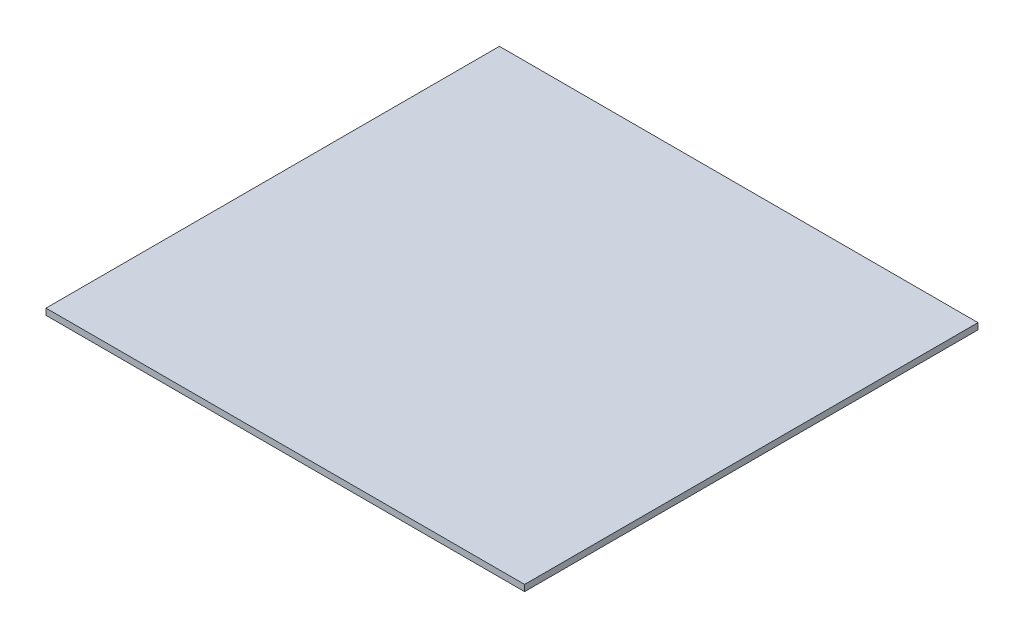
SolidWorks part; units mm, degrees
material "Teak"
ref_plane "Front Plane" through (0, 0, 0) normal (0, 0, 1) x (1, 0, 0)
ref_plane "Top Plane" through (0, 0, 0) normal (0, 1, 0) x (1, 0, 0)
ref_plane "Right Plane" through (0, 0, 0) normal (1, 0, 0) x (0, 0, -1)
sketch "Sketch1" plane through (0, 0, 0) normal (0, 1, 0) x (1, 0, 0)
  line L1 (0, 0) -> (965.2, 0)
  line L2 (0, 0) -> (0, 914.4)
  line L3 (0, 914.4) -> (965.2, 914.4)
  line L4 (965.2, 0) -> (965.2, 914.4)
  dimension "D1" = 965.2
  dimension "D2" = 914.4
extrude "Boss-Extrude1" add sketch "Sketch1" along normal blind 12.7
